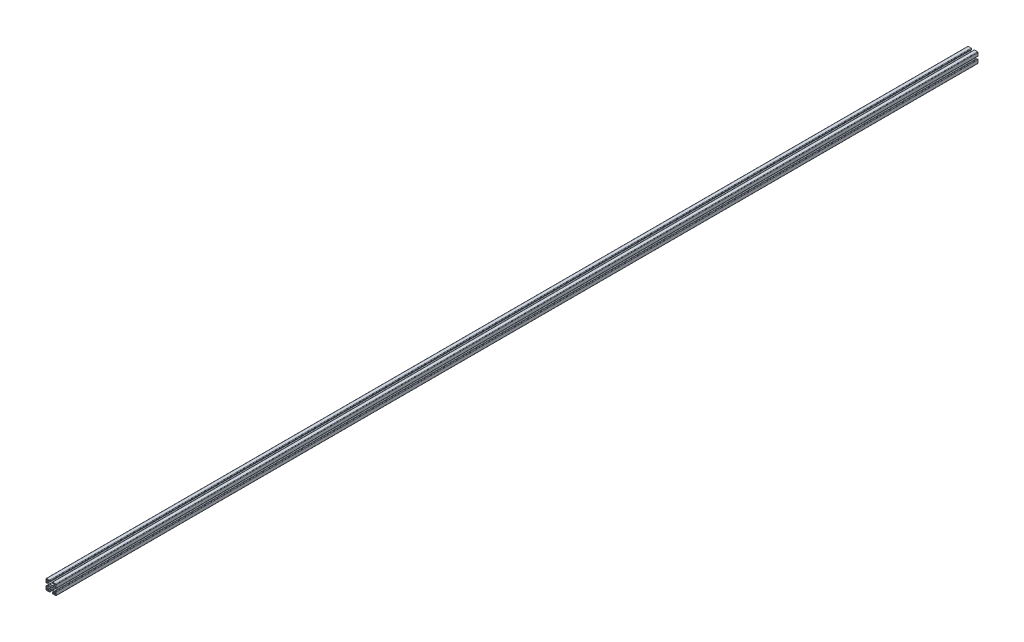
SolidWorks part; units mm, degrees
ref_plane "Alzado" through (0, 0, 0) normal (0, 0, 1) x (1, 0, 0)
ref_plane "Planta" through (0, 0, 0) normal (0, 1, 0) x (1, 0, 0)
ref_plane "Vista lateral" through (0, 0, 0) normal (1, 0, 0) x (0, 0, -1)
sketch "Croquis1" plane through (0, 0, 0) normal (0, 0, 1) x (1, 0, 0)
  line L1 (-20, -20) -> (20, -20)
  line L2 (-20, -20) -> (-20, 20)
  line L3 (-20, 20) -> (20, 20)
  line L4 (20, -20) -> (20, 20)
  line L5 (-20, -20) -> (20, 20) construction
  line L6 (-20, 20) -> (20, -20) construction
  point P0 (0, 0)
  dimension "D1" = 40
  dimension "D2" = 40
extrude "Saliente-Extruir1" add sketch "Croquis1" along normal blind 3600
sketch "Croquis2" plane through (0, 0, 3600) normal (0, 0, 1) x (1, 0, 0)
  line L0 (-7.5, 7.5) -> (-20, 20) construction
  line L1 (5.7336, -7.5014) -> (-5.7336, -7.5014)
  line L2 (7.5013, -5.7336) -> (7.5013, 5.7336)
  line L3 (5.7336, 7.5014) -> (-5.7336, 7.5014)
  line L4 (-7.5013, -5.7336) -> (-7.5013, 5.7336)
  line L5 (7.5, -7.5) -> (-7.5, 7.5) construction
  line L6 (7.5, 7.5) -> (-7.5, -7.5) construction
  line L7 (-5.7336, 7.5014) -> (-11, 12.7678)
  line L8 (-7.5013, 5.7336) -> (-12.7678, 11)
  line L9 (-20, 20) -> (-20, -20) construction
  line L10 (-18.5, 12.5) -> (-12.5, 12.5)
  line L11 (-18.5, 12.5) -> (-18.5, 18.5)
  line L12 (-18.5, 18.5) -> (-12.5, 18.5)
  line L13 (-12.5, 12.5) -> (-12.5, 18.5)
  line L14 (-18.5, 12.5) -> (-12.5, 18.5) construction
  line L15 (-18.5, 18.5) -> (-12.5, 12.5) construction
  line L16 (-11, 12.7678) -> (-11, 18)
  line L17 (-11, 18) -> (-7, 18)
  line L18 (-7, 18) -> (-7, 15.5)
  line L19 (-7, 15.5) -> (-4.5, 15.5)
  line L20 (-4.5, 15.5) -> (-4.5, 20)
  line L21 (20, 20) -> (-20, 20) construction
  line L22 (0, 20) -> (0, -20) construction
  line L23 (-20, -20) -> (20, -20) construction
  line L24 (-12.7678, 11) -> (-17.8676, 11)
  line L25 (-17.8676, 11) -> (-17.8676, 7)
  line L26 (-17.8676, 7) -> (-15.3676, 7)
  line L27 (-15.3676, 7) -> (-15.3676, 4.5)
  line L28 (-15.3676, 4.5) -> (-20, 4.5)
  line L29 (18.5, 18.5) -> (12.5, 12.5) construction
  line L30 (18.5, 12.5) -> (12.5, 18.5) construction
  line L31 (7.5, 7.5) -> (20, 20) construction
  line L32 (15.3676, 4.5) -> (20, 4.5)
  line L33 (15.3676, 7) -> (15.3676, 4.5)
  line L34 (17.8676, 7) -> (15.3676, 7)
  line L35 (17.8676, 11) -> (17.8676, 7)
  line L36 (12.7678, 11) -> (17.8676, 11)
  line L37 (4.5, 15.5) -> (4.5, 20)
  line L38 (7, 15.5) -> (4.5, 15.5)
  line L39 (7, 18) -> (7, 15.5)
  line L40 (11, 18) -> (7, 18)
  line L41 (11, 12.7678) -> (11, 18)
  line L42 (12.5, 12.5) -> (12.5, 18.5)
  line L43 (18.5, 18.5) -> (12.5, 18.5)
  line L44 (18.5, 12.5) -> (18.5, 18.5)
  line L45 (18.5, 12.5) -> (12.5, 12.5)
  line L46 (7.5013, 5.7336) -> (12.7678, 11)
  line L47 (5.7336, 7.5014) -> (11, 12.7678)
  line L48 (20, 0) -> (-20, 0) construction
  line L49 (20, -20) -> (20, 20) construction
  line L50 (7.5, -7.5) -> (20, -20) construction
  line L51 (18.5, -12.5) -> (12.5, -18.5) construction
  line L52 (18.5, -18.5) -> (12.5, -12.5) construction
  line L53 (-18.5, -18.5) -> (-12.5, -12.5) construction
  line L54 (-18.5, -12.5) -> (-12.5, -18.5) construction
  line L55 (-7.5, -7.5) -> (-20, -20) construction
  line L56 (5.7336, -7.5014) -> (11, -12.7678)
  line L57 (7.5013, -5.7336) -> (12.7678, -11)
  line L58 (18.5, -12.5) -> (12.5, -12.5)
  line L59 (18.5, -12.5) -> (18.5, -18.5)
  line L60 (18.5, -18.5) -> (12.5, -18.5)
  line L61 (12.5, -12.5) -> (12.5, -18.5)
  line L62 (11, -12.7678) -> (11, -18)
  line L63 (11, -18) -> (7, -18)
  line L64 (7, -18) -> (7, -15.5)
  line L65 (7, -15.5) -> (4.5, -15.5)
  line L66 (4.5, -15.5) -> (4.5, -20)
  line L67 (12.7678, -11) -> (17.8676, -11)
  line L68 (17.8676, -11) -> (17.8676, -7)
  line L69 (17.8676, -7) -> (15.3676, -7)
  line L70 (15.3676, -7) -> (15.3676, -4.5)
  line L71 (15.3676, -4.5) -> (20, -4.5)
  line L72 (-15.3676, -4.5) -> (-20, -4.5)
  line L73 (-15.3676, -7) -> (-15.3676, -4.5)
  line L74 (-17.8676, -7) -> (-15.3676, -7)
  line L75 (-17.8676, -11) -> (-17.8676, -7)
  line L76 (-12.7678, -11) -> (-17.8676, -11)
  line L77 (-4.5, -15.5) -> (-4.5, -20)
  line L78 (-7, -15.5) -> (-4.5, -15.5)
  line L79 (-7, -18) -> (-7, -15.5)
  line L80 (-11, -18) -> (-7, -18)
  line L81 (-11, -12.7678) -> (-11, -18)
  line L82 (-12.5, -12.5) -> (-12.5, -18.5)
  line L83 (-18.5, -18.5) -> (-12.5, -18.5)
  line L84 (-18.5, -12.5) -> (-18.5, -18.5)
  line L85 (-18.5, -12.5) -> (-12.5, -12.5)
  line L86 (-7.5013, -5.7336) -> (-12.7678, -11)
  line L87 (-5.7336, -7.5014) -> (-11, -12.7678)
  line L88 (5.7336, -7.5014) -> (-5.7336, -7.5014)
  line L89 (-20, -4.5) -> (-20, 4.5)
  line L90 (20, 4.5) -> (20, -4.5)
  line L91 (-4.5, -20) -> (4.5, -20)
  line L92 (-4.5, 20) -> (4.5, 20)
  circle A0 centre (0, 0) radius 3.5
  point P0 (0, 0)
  point P14 (-15.5, 15.5)
  point P56 (15.5, 15.5)
  point P99 (15.5, -15.5)
  point P100 (-15.5, -15.5)
  line M20 (20, -20) -> (20, 20)
  line M21 (20, 20) -> (-20, 20)
  line M22 (-20, 20) -> (-20, -20)
  line M23 (-20, -20) -> (20, -20)
  dimension "D3" = 7
  dimension "D1" = 15
  dimension "D2" = 15
  dimension "D4" = 1.25
  dimension "D5" = 1.25
  dimension "D6" = 1.5
  dimension "D7" = 6
  dimension "D8" = 6
  dimension "D9" = 1.5
  dimension "D10" = 2
  dimension "D11" = 4
  dimension "D12" = 2.5
  dimension "D13" = 2.5
  dimension "D14" = 1.5
  dimension "D15" = 4
  dimension "D16" = 2.5
  dimension "D17" = 2.5
extrude "Cortar-Extruir2" cut sketch "Croquis2" against normal up to surface (3600 mm away) contours L10 L13 L12 L11 | L3 L47 L41 L40 L39 L38 L37 L20 L19 L18 L17 L16 L7 M21 | L45 L44 L43 L42 | L70 L71 L32 L33 L34 L35 L36 L46 L2 L57 L67 L68 L69 M20 | L86 L4 L8 L24 L25 L26 L27 L28 L72 L73 L74 L75 L76 M22 | A0 | L1 L87 L81 L80 L79 L78 L77 L66 L65 L64 L63 L62 L56 M23 | L85 L84 L83 L82 | L58 L61 L60 L59 up to face at (0, 0, 0)
fillet "Redondeo1" radius 2 4 edges at (-20, -20, 1800) (-20, 20, 1800) (20, -20, 1800) (20, 20, 1800)
fillet "Redondeo2" radius 2 8 edges at (-20, -4.5, 1800) (-20, 4.5, 1800) (-4.5, -20, 1800) (4.5, -20, 1800) (20, 4.5, 1800) (20, -4.5, 1800) (4.5, 20, 1800) (-4.5, 20, 1800)
